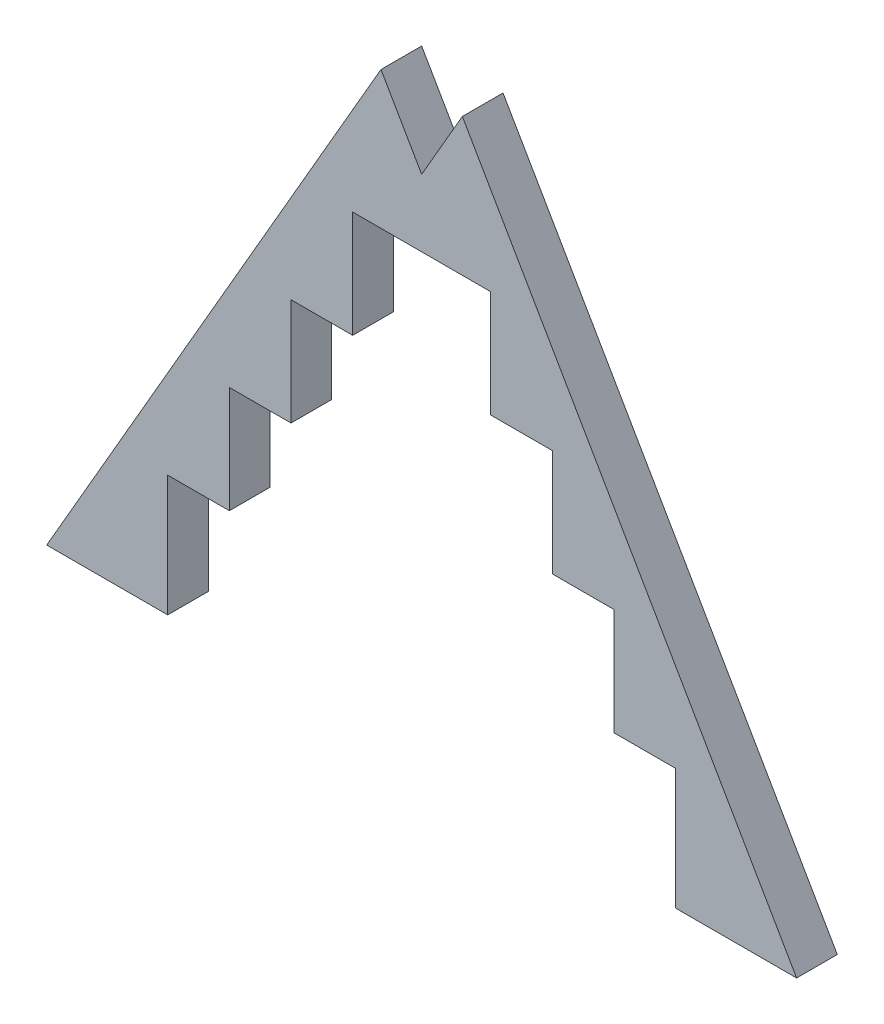
SolidWorks part; units mm, degrees
ref_plane "前视基准面" through (0, 0, 0) normal (0, 0, 1) x (1, 0, 0)
ref_plane "上视基准面" through (0, 0, 0) normal (0, 1, 0) x (1, 0, 0)
ref_plane "右视基准面" through (0, 0, 0) normal (1, 0, 0) x (0, 0, -1)
sketch "草图1" plane through (0, 0, 0) normal (0, 0, 1) x (1, 0, 0)
  line L0 (0, 20.4122) -> (-11.785, 0) construction
  line L1 (-11.785, 0) -> (11.785, 0) construction
  line L2 (11.785, 0) -> (0, 20.4122) construction
  line L3 (-2.6917, 21) -> (2.6917, 21) construction
  line L4 (-2.6917, 21) -> (-2.6917, 15.75) construction
  line L5 (-2.6917, 15.75) -> (-5.7228, 15.75) construction
  line L6 (-5.7228, 15.75) -> (-5.7228, 10.5) construction
  line L7 (-5.7228, 10.5) -> (-8.7539, 10.5) construction
  line L8 (-8.7539, 10.5) -> (-8.7539, 5.25) construction
  line L9 (-8.7539, 5.25) -> (-11.785, 5.25) construction
  line L10 (-11.785, 5.25) -> (-11.785, 0) construction
  line L11 (0, 0) -> (0, 23.214) construction
  line L12 (-11.785, 0) -> (11.785, 0) construction
  line L13 (0, -55) -> (0, 55) construction
  line L14 (0, 20.4122) -> (11.785, 0) construction
  line L15 (11.785, 5.25) -> (11.785, 0) construction
  line L16 (8.7539, 5.25) -> (11.785, 5.25) construction
  line L17 (8.7539, 10.5) -> (8.7539, 5.25) construction
  line L18 (5.7228, 10.5) -> (8.7539, 10.5) construction
  line L19 (5.7228, 15.75) -> (5.7228, 10.5) construction
  line L20 (2.6917, 15.75) -> (5.7228, 15.75) construction
  line L21 (2.6917, 21) -> (2.6917, 15.75) construction
  line L22 (-12.485, 5.95) -> (-12.485, 0)
  line L23 (-9.4539, 5.95) -> (-12.485, 5.95)
  line L24 (-9.4539, 11.2) -> (-9.4539, 5.95)
  line L25 (-6.4228, 11.2) -> (-9.4539, 11.2)
  line L26 (-6.4228, 16.45) -> (-6.4228, 11.2)
  line L27 (-3.3917, 16.45) -> (-6.4228, 16.45)
  line L28 (-3.3917, 21.7) -> (-3.3917, 16.45)
  line L29 (-3.3917, 21.7) -> (3.3917, 21.7)
  line L30 (3.3917, 21.7) -> (3.3917, 16.45)
  line L31 (3.3917, 16.45) -> (6.4228, 16.45)
  line L32 (6.4228, 16.45) -> (6.4228, 11.2)
  line L33 (6.4228, 11.2) -> (9.4539, 11.2)
  line L34 (9.4539, 11.2) -> (9.4539, 5.95)
  line L35 (9.4539, 5.95) -> (12.485, 5.95)
  line L36 (12.485, 5.95) -> (12.485, 0)
  line L37 (-2, 28.4641) -> (-18.4338, 0)
  line L38 (-18.4338, 0) -> (-12.485, 0)
  line L39 (-2, 28.4641) -> (0, 25)
  line L40 (18.4338, 0) -> (12.485, 0)
  line L41 (2, 28.4641) -> (0, 25)
  line L42 (2, 28.4641) -> (18.4338, 0)
  point P17 (0, 0)
  point P24 (0, 21)
  point P40 (-4.5417, 32.8665)
  dimension "D1" = 0.7
  dimension "D2" = 11.785
  dimension "D3" = 60
  dimension "D4" = 21
  dimension "D5" = 5.25
  dimension "D6" = 5.25
  dimension "D7" = 5.25
  dimension "D8" = 60
  dimension "D9" = 60
  dimension "D10" = 25
  dimension "D11" = 2
extrude "凸台-拉伸1" add sketch "草图1" along normal blind 2
